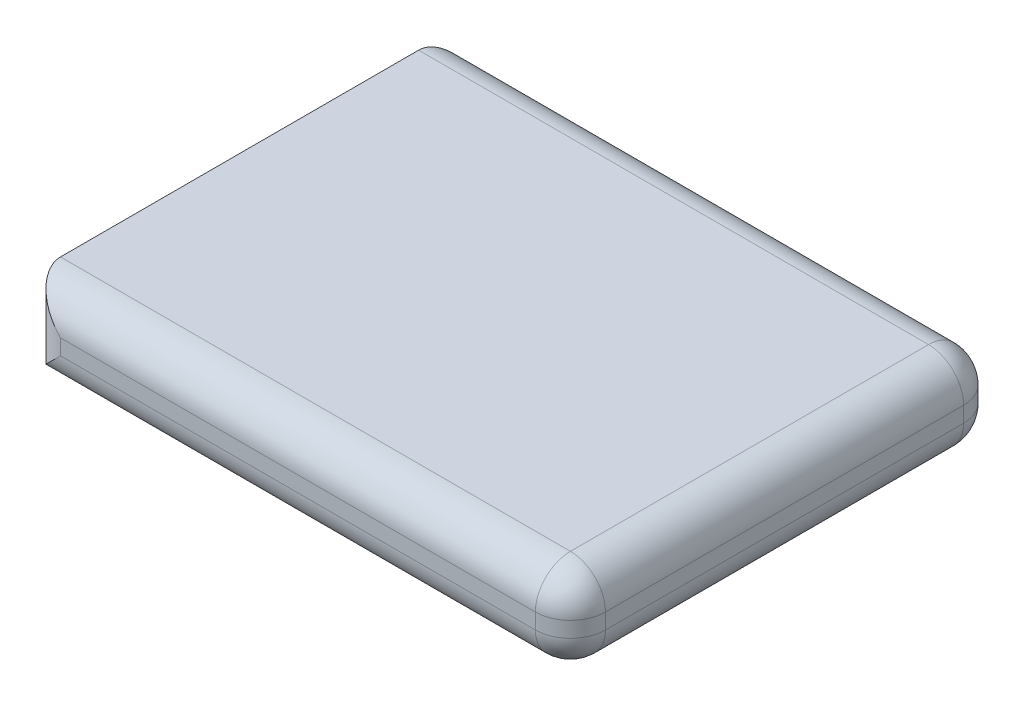
SolidWorks part; units mm, degrees
ref_plane "Front Plane" through (0, 0, 0) normal (0, 0, 1) x (1, 0, 0)
ref_plane "Top Plane" through (0, 0, 0) normal (0, 1, 0) x (1, 0, 0)
ref_plane "Right Plane" through (0, 0, 0) normal (1, 0, 0) x (0, 0, -1)
sketch "Sketch1" plane through (0, 0, 0) normal (0, 1, 0) x (1, 0, 0)
  line L1 (-35, -27.5) -> (35, -27.5)
  line L2 (-35, -27.5) -> (-35, 27.5)
  line L3 (-35, 27.5) -> (35, 27.5)
  line L4 (35, -27.5) -> (35, 27.5)
  line L5 (-35, -27.5) -> (35, 27.5) construction
  line L6 (-35, 27.5) -> (35, -27.5) construction
  point P0 (0, 0)
  dimension "D1" = 70
  dimension "D2" = 55
extrude "Boss-Extrude1" add sketch "Sketch1" along normal mid plane 11
fillet "Fillet1" radius 4.5 10 edges at (0, 5.5, -27.5) (-35, 0, -27.5) (0, -5.5, -27.5) (35, 5.5, 0) (35, 0, -27.5) (35, -5.5, 0) (-35, 0, 27.5) (0, 5.5, 27.5) (35, 0, 27.5) (0, -5.5, 27.5)
